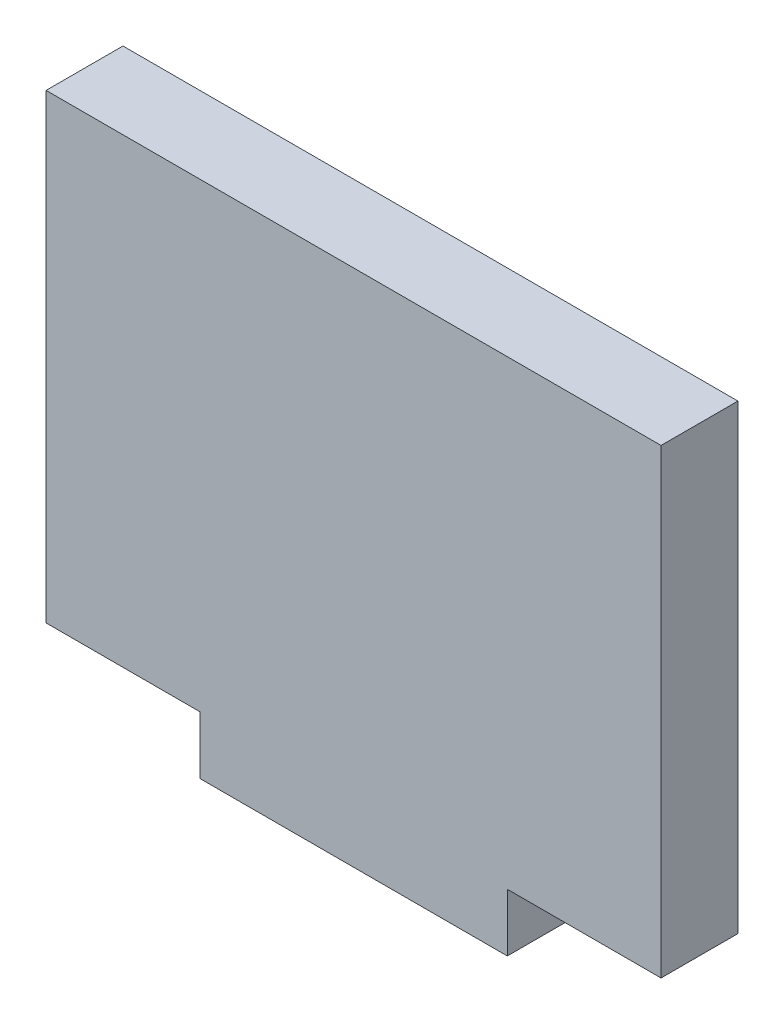
SolidWorks part; units mm, degrees
ref_plane "Front Plane" through (0, 0, 0) normal (0, 0, 1) x (1, 0, 0)
ref_plane "Top Plane" through (0, 0, 0) normal (0, 1, 0) x (1, 0, 0)
ref_plane "Right Plane" through (0, 0, 0) normal (1, 0, 0) x (0, 0, -1)
sketch "Sketch1" plane through (0, 0, 0) normal (0, 0, 1) x (1, 0, 0)
  line L0 (6.35, 0) -> (6.35, -2.3879)
  line L1 (0, 0) -> (6.35, 0)
  line L2 (0, 0) -> (0, 19.05)
  line L3 (0, 19.05) -> (25.4, 19.05)
  line L4 (25.4, 0) -> (25.4, 19.05)
  line L5 (6.35, -2.3879) -> (19.05, -2.3879)
  line L6 (19.05, -2.3879) -> (19.05, 0)
  line L7 (12.7, -2.3879) -> (12.7, 0) construction
  line L8 (19.05, 0) -> (25.4, 0)
  dimension "D1" = 25.4
  dimension "D2" = 19.05
  dimension "D3" = 12.7
extrude "Boss-Extrude1" add sketch "Sketch1" along normal blind 3.175
